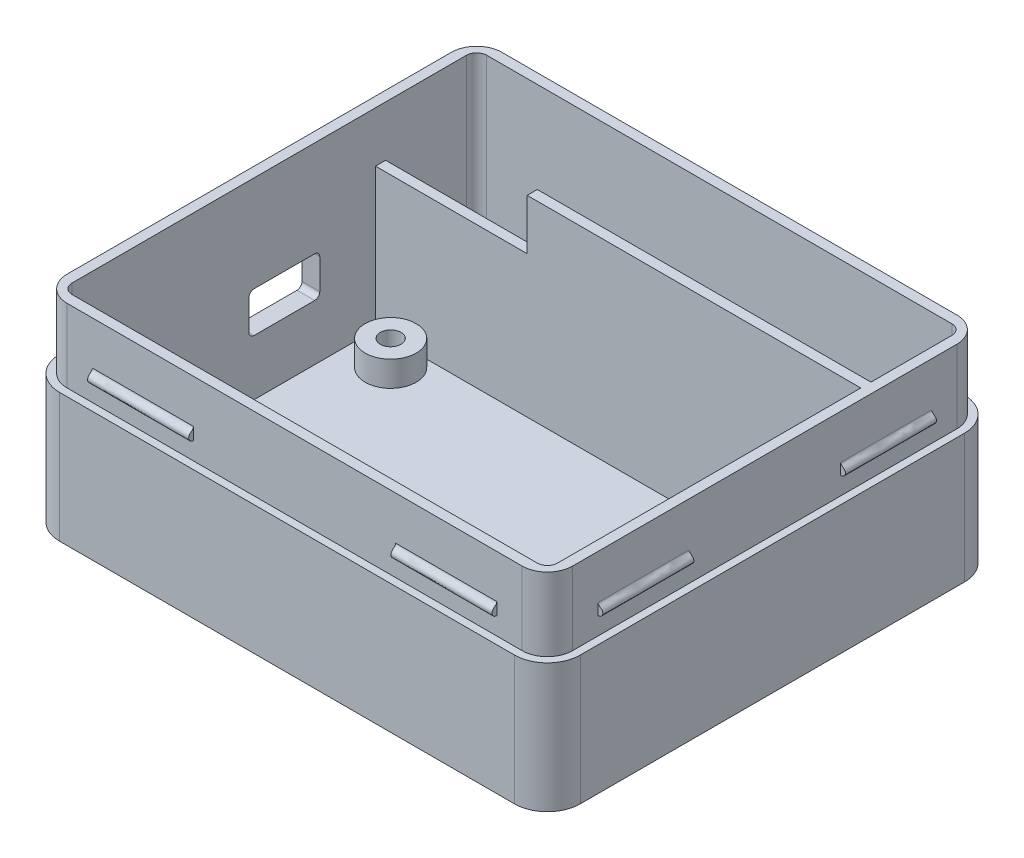
SolidWorks part; units mm, degrees
ref_plane "Plan de face" through (0, 0, 0) normal (0, 0, 1) x (1, 0, 0)
ref_plane "Plan de dessus" through (0, 0, 0) normal (0, 1, 0) x (1, 0, 0)
ref_plane "Plan de droite" through (0, 0, 0) normal (1, 0, 0) x (0, 0, -1)
sketch "Esquisse1" plane through (0, 0, 0) normal (0, 1, 0) x (1, 0, 0)
  line L1 (-50, -33) -> (50, -33)
  line L2 (-50, -33) -> (-50, 33)
  line L3 (-50, 33) -> (50, 33)
  line L4 (50, -33) -> (50, 33)
  line L5 (-50, -33) -> (50, 33) construction
  line L6 (-50, 33) -> (50, -33) construction
  point P0 (0, 0)
  dimension "D1" = 100
  dimension "D2" = 66
extrude "Boss.-Extru.1" add sketch "Esquisse1" along normal blind 40
shell "Coque1" thickness 2
sketch "Esquisse2" plane through (0, 0, 0) normal (0, -1, 0) x (1, 0, 0)
  line L0 (-50, -33) -> (-50, -53)
  line L1 (-50, -53) -> (50, -53)
  line L2 (50, -53) -> (50, -33)
  line L3 (48, -33) -> (48, -51)
  line L4 (50, -33) -> (-50, -33) construction
  line L5 (48, -51) -> (-48, -51)
  line L6 (-48, -51) -> (-48, -33)
  line L7 (48, 31) -> (48, -31) construction
  line L8 (-48, -31) -> (-48, 31) construction
  line L9 (50, -33) -> (48, -33)
  line L10 (-48, -33) -> (-50, -33)
  line L11 (50, -33) -> (-50, -33) construction
  dimension "D1" = 2
  dimension "D2" = 20
extrude "Boss.-Extru.2" add sketch "Esquisse2" against normal up to surface (40 mm away) up to face at (0, 40, 0)
sketch "Esquisse3" plane through (0, 0, 0) normal (0, -1, 0) x (1, 0, 0)
  line L0 (48, -33) -> (48, -51) construction
  line L1 (48, -51) -> (-48, -51) construction
  line L2 (-48, -51) -> (-48, -33) construction
  line L3 (48, -33) -> (-48, -33) construction
  line L4 (48, -33) -> (48, -51)
  line L5 (48, -51) -> (-48, -51)
  line L6 (-48, -51) -> (-48, -33)
  line L7 (48, -33) -> (-48, -33)
extrude "Boss.-Extru.3" add sketch "Esquisse3" against normal up to surface (2 mm away) up to face at (0, 2, 0)
fillet "Congé1" radius 2 4 edges at (48, 21, 31) (-48, 21, 31) (48, 21, -51) (-48, 21, -51)
fillet "Congé2" radius 5 4 edges at (-50, 20, -53) (50, 20, -53) (-50, 20, 33) (50, 20, 33)
sketch "Esquisse4" plane through (50, 0, 0) normal (1, 0, 0) x (0, 0, -1)
  line L0 (-35.6696, 30) -> (53.7991, 30) construction
  line L1 (-28, 40) -> (48, 40) construction
  line L2 (-33, 0) -> (-33, 40) construction
  line L3 (-33, 31) -> (-33, 29)
  line L4 (-33, 31.4075) -> (-33, 31)
  arc A0 (-33, 31) -> (-33, 29) centre (-33, 30) ccw
  spline S0 degree 3 poles (-33, 31.4075) (-33.0425, 31.15) (-33.2236, 30.8841) (-34.1997, 30.2854) (-33.9785, 29.0681) (-33, 29) knots 0 0 0 0 0.176065 0.395847 1 1 1 1
  dimension "D2" = 1
  dimension "D1" = 10
extrude "Boss.-Extru.4" add sketch "Esquisse4" against normal blind 80 from offset 10 contours L4 S0 A0 | S0 L0 L3 A0 | L0 S0 A0 L3 offset against normal yes
ref_plane "Plan1" through (0, 0, -10) normal (0, 0, -1) x (-1, 0, 0)
mirror "Symétrie1" about plane through (0, 0, -10) normal (0, 0, -1) of "Boss.-Extru.4"
sketch "Esquisse5" plane through (0, 0, -53) normal (0, 0, -1) x (-1, 0, 0)
  line L0 (41.1298, 30) -> (54.9121, 30) construction
  line L1 (-45, 40) -> (45, 40) construction
  line L2 (50, 40) -> (50, 0) construction
  line L3 (50, 31) -> (50, 29)
  line L4 (50, 31.2379) -> (50, 31)
  arc A0 (50, 29) -> (50, 31) centre (50, 30) ccw
  spline S0 degree 3 poles (50, 31.2379) (50.0069, 31.0348) (50.2661, 30.7996) (50.7334, 30.4833) (50.9408, 30.1253) (50.9918, 29.7067) (50.8246, 29.0937) (50, 29) knots 0 0 0 0 0.175751 0.513306 0.658258 0.706927 1 1 1 1
  dimension "D2" = 1
  dimension "D1" = 10
extrude "Boss.-Extru.5" add sketch "Esquisse5" against normal blind 66 from offset 10 contours S0 L4 A0 | L3 L0 S0 A0 | L0 L3 S0 A0 offset against normal yes
mirror "Symétrie2" about plane through (0, 0, 0) normal (1, 0, 0) of "Boss.-Extru.5"
sketch "Esquisse6" plane through (0, 0, -31) normal (0, 0, 1) x (1, 0, 0)
  line L1 (-48, 40) -> (-18, 40)
  line L2 (-48, 40) -> (-48, 30)
  line L3 (-48, 30) -> (-18, 30)
  line L4 (-18, 40) -> (-18, 30)
  dimension "D1" = 30
  dimension "D2" = 10
extrude "Enlèv. mat.-Extru.1" cut sketch "Esquisse6" against normal blind 5
sketch "Esquisse7" plane through (0, 2, 0) normal (0, 1, 0) x (1, 0, 0)
  line L0 (-40, 30) -> (-40, -23) construction
  line L1 (32, 31) -> (32, -31) construction
  line L2 (48, -29) -> (48, 31) construction
  line L3 (48, 31) -> (-48, 31) construction
  line L4 (-46, -31) -> (46, -31) construction
  line L5 (48, 31) -> (-18, 31) construction
  circle A0 centre (-40, 26) radius 5.05
  circle A1 centre (-40, -23) radius 5
  circle A2 centre (32, -17) radius 5
  circle A3 centre (32, 11) radius 5
  dimension "D4" = 10.1
  dimension "D5" = 10
  dimension "D8" = 10
  dimension "D9" = 10
  dimension "D1" = 72
  dimension "D2" = 16
  dimension "D3" = 49
  dimension "D6" = 5
  dimension "D7" = 6
  dimension "D10" = 28
extrude "Boss.-Extru.6" add sketch "Esquisse7" along normal blind 5
sketch "Esquisse8" plane through (0, 7, 0) normal (0, 1, 0) x (1, 0, 0)
  circle A0 centre (-40, 26) radius 2.05
  circle A1 centre (-40, -23) radius 2.05
  circle A2 centre (32, 11) radius 2.05
  circle A3 centre (32, -17) radius 2.05
  dimension "D1" = 4.1
  dimension "D2" = 4.1
  dimension "D3" = 4.1
  dimension "D4" = 4.1
extrude "Enlèv. mat.-Extru.2" cut sketch "Esquisse8" against normal blind 6.5
sketch "Esquisse9" plane through (0, 0, 0) normal (0, -1, 0) x (1, 0, 0)
  line L1 (-36.7361, 23.7486) -> (-39.0163, 26.2009)
  line L2 (-39.0163, 26.2009) -> (-42.2802, 25.4523)
  line L3 (-42.2802, 25.4523) -> (-43.2639, 22.2514)
  line L4 (-43.2639, 22.2514) -> (-40.9837, 19.7991)
  line L5 (-40.9837, 19.7991) -> (-37.7198, 20.5477)
  line L6 (-37.7198, 20.5477) -> (-36.7361, 23.7486)
  line L7 (35.2639, 17.7486) -> (32.9837, 20.2009)
  line L8 (32.9837, 20.2009) -> (29.7198, 19.4523)
  line L9 (29.7198, 19.4523) -> (28.7361, 16.2514)
  line L10 (28.7361, 16.2514) -> (31.0163, 13.7991)
  line L11 (31.0163, 13.7991) -> (34.2802, 14.5477)
  line L12 (34.2802, 14.5477) -> (35.2639, 17.7486)
  line L13 (35.2639, -10.2514) -> (32.9837, -7.7991)
  line L14 (32.9837, -7.7991) -> (29.7198, -8.5477)
  line L15 (29.7198, -8.5477) -> (28.7361, -11.7486)
  line L16 (28.7361, -11.7486) -> (31.0163, -14.2009)
  line L17 (31.0163, -14.2009) -> (34.2802, -13.4523)
  line L18 (34.2802, -13.4523) -> (35.2639, -10.2514)
  line L19 (-36.7361, -25.2514) -> (-39.0163, -22.7991)
  line L20 (-39.0163, -22.7991) -> (-42.2802, -23.5477)
  line L21 (-42.2802, -23.5477) -> (-43.2639, -26.7486)
  line L22 (-43.2639, -26.7486) -> (-40.9837, -29.2009)
  line L23 (-40.9837, -29.2009) -> (-37.7198, -28.4523)
  line L24 (-37.7198, -28.4523) -> (-36.7361, -25.2514)
  circle A0 centre (-40, 23) radius 2.9 construction
  circle A1 centre (32, 17) radius 2.9 construction
  circle A2 centre (32, -11) radius 2.9 construction
  circle A3 centre (-40, -26) radius 2.9 construction
  dimension "D3" = 5.8
  dimension "D4" = 5.8
  dimension "D1" = 5.8
  dimension "D2" = 5.8
extrude "Enlèv. mat.-Extru.3" [suppressed] cut sketch "Esquisse9" against normal blind 2.5
sketch "Esquisse10" plane through (0, 0, 0) normal (0, -1, 0) x (1, 0, 0)
  line L4 (50, 28) -> (50, -48) construction
  line L5 (-45, -53) -> (45, -53) construction
  line L6 (-50, -48) -> (-50, 28) construction
  line L7 (-45, 33) -> (45, 33) construction
  line L8 (-51.5, 28) -> (-51.5, -48)
  line L16 (50, 28) -> (50, -48)
  line L17 (-45, -53) -> (45, -53)
  line L18 (-50, -48) -> (-50, 28)
  line L19 (-45, 33) -> (45, 33)
  line L40 (-51.5, 28) -> (-51.5, -48)
  line L44 (-45, -54.5) -> (45, -54.5)
  line L46 (-45, -54.5) -> (45, -54.5)
  line L48 (51.5, -48) -> (51.5, 28)
  line L49 (51.5, -48) -> (51.5, 28)
  line L50 (45, 34.5) -> (-45, 34.5)
  line L51 (45, 34.5) -> (-45, 34.5)
  arc A4 (50, 28) -> (45, 33) centre (45, 28) ccw construction
  arc A5 (45, -53) -> (50, -48) centre (45, -48) ccw construction
  arc A6 (-50, -48) -> (-45, -53) centre (-45, -48) ccw construction
  arc A7 (-45, 33) -> (-50, 28) centre (-45, 28) ccw construction
  arc A8 (-51.5, -48) -> (-45, -54.5) centre (-45, -48) ccw
  arc A16 (50, 28) -> (45, 33) centre (45, 28) ccw
  arc A17 (45, -53) -> (50, -48) centre (45, -48) ccw
  arc A18 (-50, -48) -> (-45, -53) centre (-45, -48) ccw
  arc A19 (-45, 33) -> (-50, 28) centre (-45, 28) ccw
  arc A40 (-51.5, -48) -> (-45, -54.5) centre (-45, -48) ccw
  arc A44 (45, -54.5) -> (51.5, -48) centre (45, -48) ccw
  arc A46 (45, -54.5) -> (51.5, -48) centre (45, -48) ccw
  arc A48 (51.5, 28) -> (45, 34.5) centre (45, 28) ccw
  arc A49 (51.5, 28) -> (45, 34.5) centre (45, 28) ccw
  arc A50 (-45, 34.5) -> (-51.5, 28) centre (-45, 28) ccw
  arc A51 (-45, 34.5) -> (-51.5, 28) centre (-45, 28) ccw
  dimension "D1" = 1.5
extrude "Boss.-Extru.7" add sketch "Esquisse10" against normal blind 25.5
sketch "Esquisse11" plane through (-48, 0, 0) normal (1, 0, 0) x (0, 0, -1)
  line L0 (31, 7) -> (20.95, 7) construction
  line L1 (5.975, 13) -> (19.975, 13)
  line L2 (5.975, 13) -> (5.975, 21)
  line L3 (5.975, 21) -> (19.975, 21)
  line L4 (19.975, 13) -> (19.975, 21)
  line L5 (5.975, 13) -> (19.975, 21) construction
  line L6 (5.975, 21) -> (19.975, 13) construction
  line L7 (25.975, 7) -> (25.975, 18) construction
  point P0 (12.975, 17)
  dimension "D1" = 8
  dimension "D2" = 14
  dimension "D3" = 13
  dimension "D4" = 6
extrude "Enlèv. mat.-Extru.4" cut sketch "Esquisse11" against normal blind 10
fillet "Congé3" radius 1 4 edges at (-49.75, 13, -5.975) (-49.75, 13, -19.975) (-49.75, 21, -5.975) (-49.75, 21, -19.975)
sketch "Esquisse12" plane through (-48, 0, 0) normal (1, 0, 0) x (0, 0, -1)
  line L0 (31, 7) -> (20.95, 7) construction
  line L1 (-9.025, 34.5) -> (16.975, 34.5)
  line L2 (-9.025, 34.5) -> (-9.025, 30.5)
  line L3 (-9.025, 30.5) -> (16.975, 30.5)
  line L4 (16.975, 34.5) -> (16.975, 30.5)
  line L5 (-9.025, 34.5) -> (16.975, 30.5) construction
  line L6 (-9.025, 30.5) -> (16.975, 34.5) construction
  point P0 (3.975, 32.5)
  point P9 (25.975, 7)
  dimension "D1" = 23.5
  dimension "D2" = 9
  dimension "D3" = 26
  dimension "D4" = 4
extrude "Enlèv. mat.-Extru.5" [suppressed] cut sketch "Esquisse12" against normal blind 10
sketch "Esquisse13" plane through (0, 40, 0) normal (0, 1, 0) x (1, 0, 0)
  line L0 (-77.5286, 10) -> (77.5286, 10) construction
  line L1 (0, 82.546) -> (0, -67.4997) construction
  line L2 (-45, 54.5) -> (45, 54.5) construction
  line L3 (45, -34.5) -> (-45, -34.5) construction
  line L4 (-50, 48) -> (-50, -28) construction
  line L5 (-65.2558, 25) -> (-50, 25)
  line L6 (-65.2558, 25) -> (-65.2558, -5)
  line L7 (-65.2558, -5) -> (-50, -5)
  line L8 (-50, 25) -> (-50, -5)
  line L9 (-65.2558, 25) -> (-50, -5) construction
  line L10 (-65.2558, -5) -> (-50, 25) construction
  line L12 (69.1875, -5) -> (50, -5)
  line L13 (69.1875, -5) -> (69.1875, 25)
  line L14 (69.1875, 25) -> (50, 25)
  line L15 (50, -5) -> (50, 25)
  line L16 (69.1875, -5) -> (50, 25) construction
  line L17 (69.1875, 25) -> (50, -5) construction
  line L18 (-45, -33) -> (45, -33) construction
  line L19 (20, -55.4756) -> (-20, -55.4756)
  line L20 (20, -55.4756) -> (20, -33)
  line L21 (20, -33) -> (-20, -33)
  line L22 (-20, -55.4756) -> (-20, -33)
  line L23 (20, -55.4756) -> (-20, -33) construction
  line L24 (20, -33) -> (-20, -55.4756) construction
  line L25 (45, 53) -> (-45, 53) construction
  line L26 (-20, 75.0317) -> (20, 75.0317)
  line L27 (-20, 75.0317) -> (-20, 53)
  line L28 (-20, 53) -> (20, 53)
  line L29 (20, 75.0317) -> (20, 53)
  line L30 (-20, 75.0317) -> (20, 53) construction
  line L31 (-20, 53) -> (20, 75.0317) construction
  point P9 (-57.6279, 10)
  point P16 (59.5938, 10)
  point P23 (0, -44.2378)
  point P30 (0, 64.0158)
  dimension "D1" = 30
  dimension "D2" = 40
extrude "Enlèv. mat.-Extru.6" cut sketch "Esquisse13" against normal up to surface (14.5 mm away)
